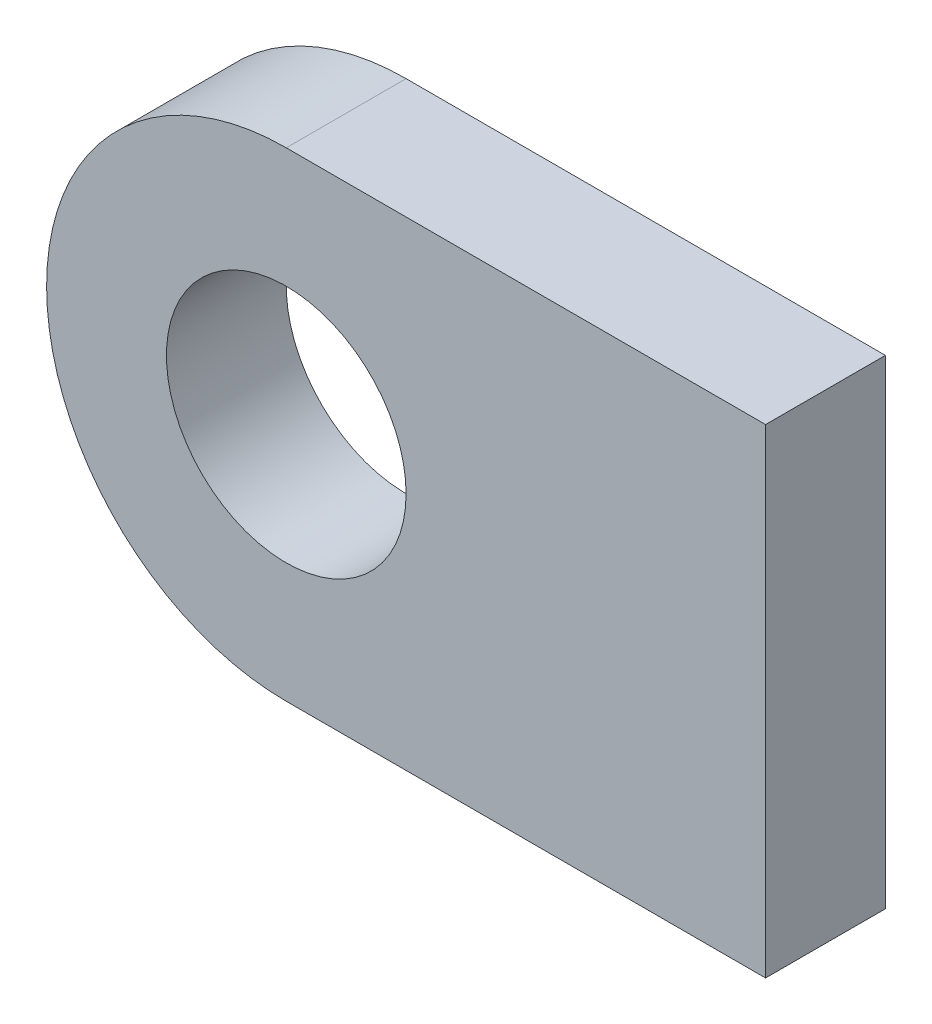
SolidWorks part; units mm, degrees
material "201 Annealed Stainless Steel (SS)"
ref_plane "Front Plane" through (0, 0, 0) normal (0, 0, 1) x (1, 0, 0)
ref_plane "Top Plane" through (0, 0, 0) normal (0, 1, 0) x (1, 0, 0)
ref_plane "Right Plane" through (0, 0, 0) normal (1, 0, 0) x (0, 0, -1)
sketch "Sketch4" plane through (0, 0, 0) normal (0, 0, 1) x (1, 0, 0)
  line L1 (-33.5489, 10) -> (-13.5489, 10)
  line L3 (-33.5489, -10) -> (-13.5489, -10)
  line L4 (-13.5489, 10) -> (-13.5489, -10)
  arc A0 (-33.5489, 10) -> (-33.5489, -10) centre (-33.5489, 0) ccw
extrude "Boss-Extrude2" add sketch "Sketch4" along normal blind 5 contours L1 L4 L3 A0
hole_wizard "Ø10.0mm Dowel Hole1" positions "Sketch9" profile "Sketch10" hole size "Ø10.0" standard "ANSI Metric"
sketch "Sketch9" plane through (0, 0, 5) normal (0, 0, 1) x (1, 0, 0)
  point P0 (-33.5489, 0)
sketch "Sketch10" plane through (-33.5489, 0, 5) normal (1, 0, 0) x (0, -1, 0)
  line L0 (0, 0) -> (0, 13.0043)
  line L1 (0, 13.0043) -> (5, 10)
  line L2 (5, 10) -> (5, 0)
  line L5 (5, 0) -> (0, 0)
  line L10 (0, 13.0043) -> (-5, 10) construction
  line L11 (0, -6.35) -> (0, 107.95) construction
  dimension "Hole Dia." = 10
  dimension "Hole Depth" = 10
  dimension "Drill Angle" = 118
